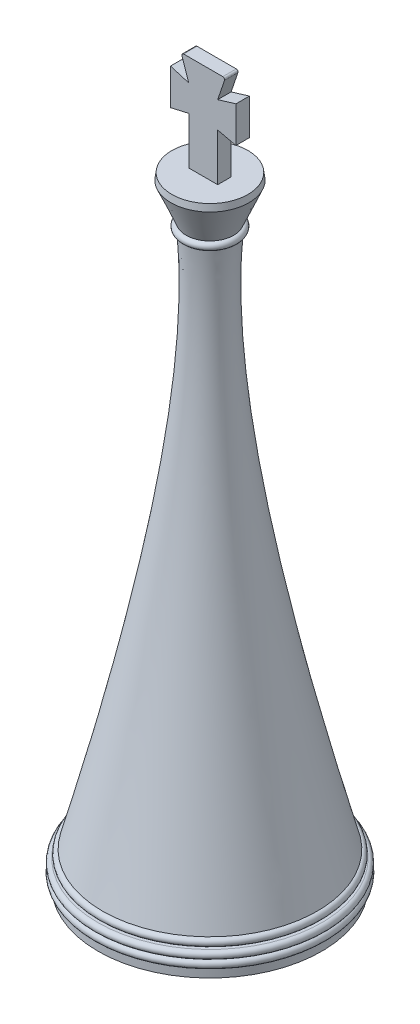
SolidWorks part; units mm, degrees
ref_plane "Front Plane" through (0, 0, 0) normal (0, 0, 1) x (1, 0, 0)
ref_plane "Top Plane" through (0, 0, 0) normal (0, 1, 0) x (1, 0, 0)
ref_plane "Right Plane" through (0, 0, 0) normal (1, 0, 0) x (0, 0, -1)
sketch "Sketch2" plane through (0, 0, 0) normal (0, 1, 0) x (1, 0, 0)
  circle A0 centre (0, 0) radius 12.5
  dimension "D1" = 25
extrude "Boss-Extrude1" add sketch "Sketch2" along normal blind 1
sketch "Sketch4" plane through (0, 0, 0) normal (0, 0, 1) x (1, 0, 0)
  line L0 (0, 0.5) -> (0, 33.453) construction
ref_plane "Plane1" through (0, 1, 0) normal (0, 1, 0) x (1, 0, 0)
sketch "Sketch9" plane through (0, 0, 0) normal (0, 0, 1) x (1, 0, 0)
  line L0 (0, 1) -> (12.5, 1)
  line L1 (12.5, 1) -> (-12.5, 1) construction
  line L2 (12.5, 1.9046) -> (0, 1.9046)
  line L3 (0, -199999.5) -> (0, 200033.453) construction
  line L4 (0, 1.9046) -> (0, 1)
  arc A0 (12.5, 1) -> (12.5, 1.9046) centre (12.5, 1.4523) ccw
revolve "Revolve1" add sketch "Sketch9" angle 360 about L4
sketch "Sketch10" plane through (0, 0, 0) normal (0, 0, 1) x (1, 0, 0)
  line L0 (0, 1.9046) -> (12.5, 1.9046)
  line L1 (12.5, 1.9046) -> (-12.5, 1.9046) construction
  line L2 (12.5, 2.7668) -> (0, 2.7668)
  line L3 (0, -199999.5) -> (0, 200033.453) construction
  line L4 (0, 2.7668) -> (0, 1.9046)
  arc A0 (12.5, 1.9046) -> (12.5, 2.7668) centre (12.5, 2.3357) ccw
revolve "Revolve2" add sketch "Sketch10" angle 360 about L4
sketch "Sketch12" plane through (0, 0, 0) normal (0, 0, 1) x (1, 0, 0)
  line L0 (0, 2.7668) -> (12, 2.7668)
  line L1 (12.5, 2.7668) -> (-12.5, 2.7668) construction
  line L5 (12, 3.634) -> (0, 3.634)
  line L6 (0, -199999.5) -> (0, 200033.453) construction
  line L7 (0, 3.634) -> (0, 2.7668)
  arc A1 (12, 2.7668) -> (12, 3.634) centre (12, 3.2004) ccw
  dimension "D1" = 12
revolve "Revolve3" add sketch "Sketch12" angle 360 about L7
sketch "Sketch13" plane through (0, 0, 0) normal (0, 0, 1) x (1, 0, 0)
  line L3 (12, 3.634) -> (0.9894, 44.9146) construction
  line L4 (0.9894, 44.9146) -> (2.6603, 63.5042) construction
  line L5 (2.6603, 63.5042) -> (0, 63.5042)
  line L6 (0, -199999.5) -> (0, 200033.453) construction
  line L7 (0, 63.5042) -> (0, 3.634)
  line L8 (12, 3.634) -> (-12, 3.634) construction
  line L9 (0, 3.634) -> (12, 3.634)
  spline S0 degree 2 poles (12, 3.634) (0.9894, 44.9146) (2.6603, 63.5042) knots 0 0 0 1 1 1
revolve "Revolve4" add sketch "Sketch13" angle 360 about L7
sketch "Sketch14" plane through (0, 0, 0) normal (0, 0, 1) x (1, 0, 0)
  line L0 (0, 63.5042) -> (2.6603, 63.5042)
  line L1 (2.6603, 63.5042) -> (-2.6603, 63.5042) construction
  line L2 (2.6603, 64.3486) -> (0, 64.3486)
  line L3 (0, -199999.5) -> (0, 200033.453) construction
  line L4 (0, 64.3486) -> (0, 63.5042)
  arc A0 (2.6603, 63.5042) -> (2.6603, 64.3486) centre (2.6603, 63.9264) ccw
revolve "Revolve5" add sketch "Sketch14" angle 360 about L4
sketch "Sketch18" plane through (0, 64.3486, 0) normal (0, 1, 0) x (1, 0, 0)
  circle A0 centre (0, 0) radius 2.6603
extrude "Boss-Extrude2" add sketch "Sketch18" along normal blind 4 draft 23 draft outward yes
sketch "Sketch22" plane through (0, 68.3486, 0) normal (0, 1, 0) x (1, 0, 0)
  circle A0 centre (0, 0) radius 4.3582
extrude "Boss-Extrude3" add sketch "Sketch22" along normal blind 0.75 draft 8
sketch "Sketch26" plane through (0, 0, 0) normal (0, 0, 1) x (1, 0, 0)
  line L6 (0, 69.0986) -> (1.6157, 69.0986)
  line L7 (4.2528, 69.0986) -> (-4.2528, 69.0986) construction
  line L8 (1.6157, 69.0986) -> (1.6157, 74.3857)
  line L9 (3.655, 73.9115) -> (3.655, 77.9426)
  line L10 (2.4694, 79.8397) -> (0, 79.8397)
  line L11 (0, -199999.5) -> (0, 200033.453) construction
  line L12 (0, 79.8397) -> (0, 69.0986)
  spline S0 degree 1 poles (1.6157, 74.3857) (3.655, 73.9115) knots 0 0 1 1
  spline S1 degree 1 poles (3.655, 77.9426) (1.6157, 77.3261) knots 0 0 1 1
  spline S2 degree 1 poles (1.6157, 77.3261) (2.4694, 79.8397) knots 0 0 1 1
extrude "Boss-Extrude6" add sketch "Sketch26" along normal mid plane 1.5
pattern_circular "CirPattern3" count 2 over 360 about axis through (0, 0.5, 0) along (0, 1, 0) of "Boss-Extrude6"
fillet "Fillet4" radius 0.2 2 edges at (2.4694, 79.8397, 0) (-2.4694, 79.8397, 0)
